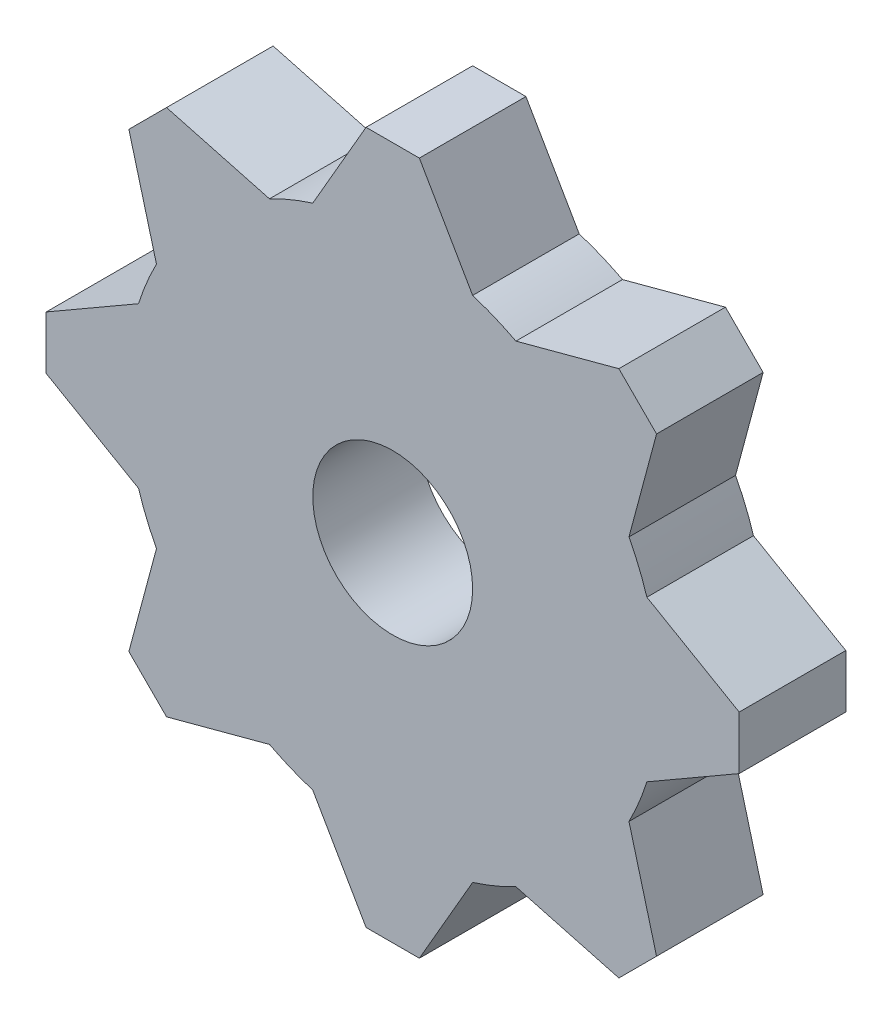
SolidWorks part; units mm, degrees
ref_plane "Płaszczyzna przednia" through (0, 0, 0) normal (0, 0, 1) x (1, 0, 0)
ref_plane "Płaszczyzna górna" through (0, 0, 0) normal (0, 1, 0) x (1, 0, 0)
ref_plane "Płaszczyzna prawa" through (0, 0, 0) normal (1, 0, 0) x (0, 0, -1)
sketch "Szkic1" plane through (0, 0, 0) normal (0, 0, 1) x (1, 0, 0)
  line L0 (0, 55.1501) -> (0, -56.3776) construction
  line L1 (-89.2072, 0) -> (93.5667, 0) construction
  line L2 (-5, 65.0175) -> (5, 65.0175)
  line L3 (5, 65.0175) -> (15, 47.697)
  line L4 (-5, 65.0175) -> (-15, 47.697)
  line L5 (42.4388, 49.5098) -> (23.1202, 44.3334)
  line L6 (42.4388, 49.5098) -> (49.5098, 42.4388)
  line L7 (49.5098, 42.4388) -> (44.3334, 23.1202)
  line L8 (65.0175, 5) -> (47.697, 15)
  line L9 (65.0175, 5) -> (65.0175, -5)
  line L10 (65.0175, -5) -> (47.697, -15)
  line L11 (49.5098, -42.4388) -> (44.3334, -23.1202)
  line L12 (49.5098, -42.4388) -> (42.4388, -49.5098)
  line L13 (42.4388, -49.5098) -> (23.1202, -44.3334)
  line L14 (5, -65.0175) -> (15, -47.697)
  line L15 (5, -65.0175) -> (-5, -65.0175)
  line L16 (-5, -65.0175) -> (-15, -47.697)
  line L17 (-42.4388, -49.5098) -> (-23.1202, -44.3334)
  line L18 (-42.4388, -49.5098) -> (-49.5098, -42.4388)
  line L19 (-49.5098, -42.4388) -> (-44.3334, -23.1202)
  line L20 (-65.0175, -5) -> (-47.697, -15)
  line L21 (-65.0175, -5) -> (-65.0175, 5)
  line L22 (-65.0175, 5) -> (-47.697, 15)
  line L23 (-49.5098, 42.4388) -> (-44.3334, 23.1202)
  line L24 (-49.5098, 42.4388) -> (-42.4388, 49.5098)
  line L25 (-42.4388, 49.5098) -> (-23.1202, 44.3334)
  circle A0 centre (0, 0) radius 15
  arc A1 (-47.697, -15) -> (-44.3334, -23.1202) centre (0, 0) ccw
  arc A2 (-44.3334, 23.1202) -> (-47.697, 15) centre (0, 0) ccw
  arc A3 (-15, 47.697) -> (-23.1202, 44.3334) centre (0, 0) ccw
  arc A4 (23.1202, 44.3334) -> (15, 47.697) centre (0, 0) ccw
  arc A5 (47.697, 15) -> (44.3334, 23.1202) centre (0, 0) ccw
  arc A6 (44.3334, -23.1202) -> (47.697, -15) centre (0, 0) ccw
  arc A7 (15, -47.697) -> (23.1202, -44.3334) centre (0, 0) ccw
  arc A8 (-23.1202, -44.3334) -> (-15, -47.697) centre (0, 0) ccw
  point P9 (0, 65.0175)
  point P11 (0, 0)
  point P16 (0, 0)
  point P19 (0, 0)
  point P21 (0, 0)
  point P58 (0, 0)
  dimension "D1" = 10
  dimension "Dw" = 30
  dimension "Dz" = 100
  dimension "D2" = 20
  dimension "D3" = 60
  dimension "D4" = 8
extrude "Dodanie-wyciągnięcie1" add sketch "Szkic1" along normal blind 20
